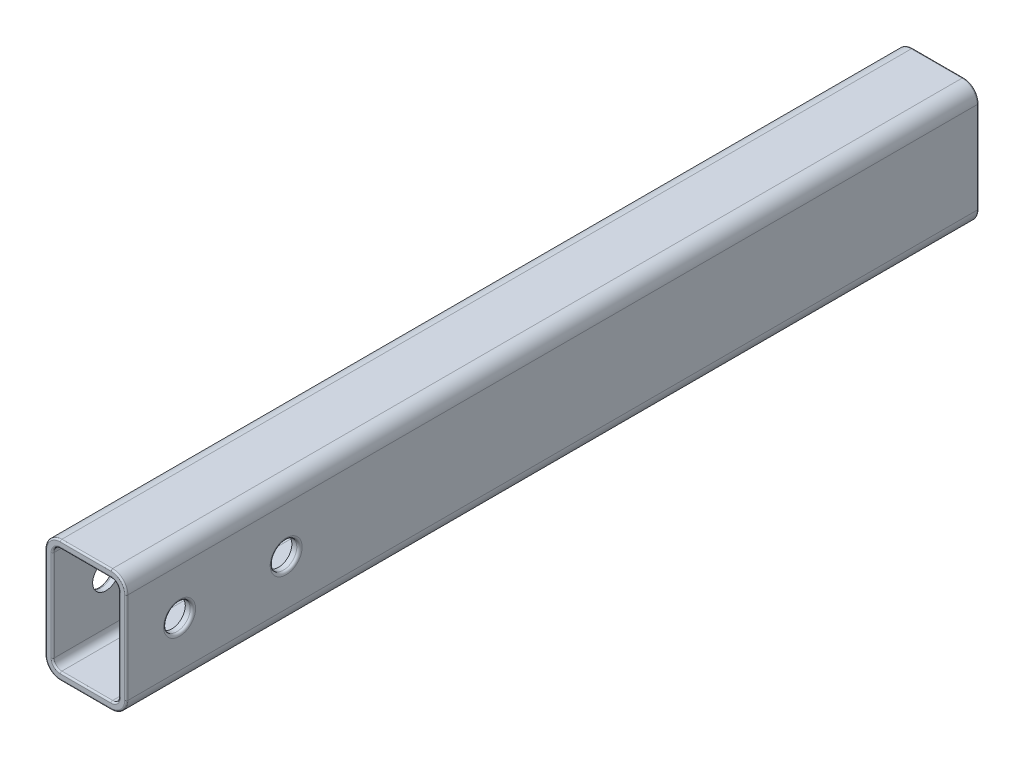
SolidWorks part; units mm, degrees
material "1.0037 (S235JR)"
ref_plane "Front Plane" through (0, 0, 0) normal (0, 0, 1) x (1, 0, 0)
ref_plane "Top Plane" through (0, 0, 0) normal (0, 1, 0) x (1, 0, 0)
ref_plane "Right Plane" through (0, 0, 0) normal (1, 0, 0) x (0, 0, -1)
sketch "Sketch1" plane through (0, 0, 0) normal (0, 1, 0) x (1, 0, 0)
  line L0 (0, 1098.3779) -> (0, -501.6221)
  dimension "D1" = 1600
ref_plane "Plane1" through (0, 0, -1098.3779) normal (0, 0, 1) x (1, 0, 0)
other "Tube rectangular TR9X6X0.5625(1)"
ref_plane "Plane2" through (0, 0, -1098.3779) normal (0, 0, 1) x (1, 0, 0)
sketch "Sketch129" plane through (0, 0, -1098.3779) normal (0, 0, 1) x (1, 0, 0)
  line L0 (-47.625, -100.0125) -> (47.625, -100.0125)
  line L1 (-61.9125, -85.725) -> (-61.9125, 85.725)
  line L2 (47.625, 100.0125) -> (-47.625, 100.0125)
  line L3 (61.9125, 85.725) -> (61.9125, -85.725)
  line L4 (-47.625, -114.3) -> (47.625, -114.3)
  line L5 (-76.2, -85.725) -> (-76.2, 85.725)
  line L6 (47.625, 114.3) -> (-47.625, 114.3)
  line L7 (76.2, 85.725) -> (76.2, -85.725)
  line L8 (0, 114.3) -> (0, 100.0125) construction
  line L9 (0, 100.0125) -> (0, -100.0125) construction
  line L10 (0, -100.0125) -> (0, -114.3) construction
  line L11 (-76.2, 0) -> (-61.9125, 0) construction
  line L12 (-61.9125, 0) -> (61.9125, 0) construction
  line L13 (61.9125, 0) -> (76.2, 0) construction
  arc A0 (76.2, 85.725) -> (47.625, 114.3) centre (47.625, 85.725) ccw
  arc A1 (47.625, -114.3) -> (76.2, -85.725) centre (47.625, -85.725) ccw
  arc A2 (-76.2, -85.725) -> (-47.625, -114.3) centre (-47.625, -85.725) ccw
  arc A3 (-47.625, 114.3) -> (-76.2, 85.725) centre (-47.625, 85.725) ccw
  arc A4 (-47.625, 100.0125) -> (-61.9125, 85.725) centre (-47.625, 85.725) ccw
  arc A5 (61.9125, 85.725) -> (47.625, 100.0125) centre (47.625, 85.725) ccw
  arc A6 (47.625, -100.0125) -> (61.9125, -85.725) centre (47.625, -85.725) ccw
  arc A7 (-61.9125, -85.725) -> (-47.625, -100.0125) centre (-47.625, -85.725) ccw
  point P6 (-76.2, 114.3)
  point P33 (76.2, 114.3)
  point P35 (-76.2, -114.3)
  point P36 (76.2, -114.3)
  point P37 (0, 0)
  point P38 (0, 0)
  dimension "D1" = 28.575
  dimension "Thickness" = 14.2875
  dimension "V_leg" = 228.6
  dimension "H_leg" = 152.4
sketch "Sketch130" plane through (76.2, 0, 0) normal (1, 0, 0) x (0, 0, -1)
  line L1 (-501.6221, -85.725) -> (-501.6221, 85.725) construction
  line L2 (1098.3779, 0) -> (-501.6221, 0) construction
  circle A0 centre (-401.6221, 0) radius 25
  circle A1 centre (-201.6221, 0) radius 25
  dimension "D1" = 50
  dimension "D2" = 50
  dimension "D3" = 100
  dimension "D4" = 200
extrude "Cut-Extrude1" cut sketch "Sketch130" against normal through all
fillet "Fillet2" radius 5 4 edges at (-76.2, 0, 376.6221) (-76.2, 0, 176.6221) (76.2, 0, 176.6221) (76.2, 0, 376.6221)
fillet "Fillet3" radius 3 32 edges at (0, 114.3, -1098.3779) (-67.8306, 105.9306, -1098.3779) (-76.2, 0, -1098.3779) (-67.8306, -105.9306, -1098.3779) (0, -114.3, -1098.3779) (67.8306, -105.9306, -1098.3779) (76.2, 0, -1098.3779) (67.8306, 105.9306, -1098.3779) (0, 100.0125, -1098.3779) (57.7278, 95.8278, -1098.3779) (61.9125, 0, -1098.3779) (57.7278, -95.8278, -1098.3779) (0, -100.0125, -1098.3779) (-57.7278, -95.8278, -1098.3779) (-61.9125, 0, -1098.3779) (-57.7278, 95.8278, -1098.3779) (76.2, 0, 501.6221) (67.8306, -105.9306, 501.6221) (0, -114.3, 501.6221) (-67.8306, -105.9306, 501.6221) (-76.2, 0, 501.6221) (-67.8306, 105.9306, 501.6221) (0, 114.3, 501.6221) (67.8306, 105.9306, 501.6221) (-61.9125, 0, 501.6221) (-57.7278, -95.8278, 501.6221) (0, -100.0125, 501.6221) (57.7278, -95.8278, 501.6221) (61.9125, 0, 501.6221) (57.7278, 95.8278, 501.6221) (0, 100.0125, 501.6221) (-57.7278, 95.8278, 501.6221)
sketch "Sketch131" plane through (-76.2, 0, 0) normal (-1, 0, 0) x (0, 0, 1)
  point P0 (201.6221, 0)
  point P2 (401.6221, 0)
ref_plane "Plane3" through (0, 0, 201.6221) normal (0, 0, 1) x (1, 0, 0)
ref_plane "Plane4" through (0, 0, 401.6221) normal (0, 0, 1) x (1, 0, 0)
